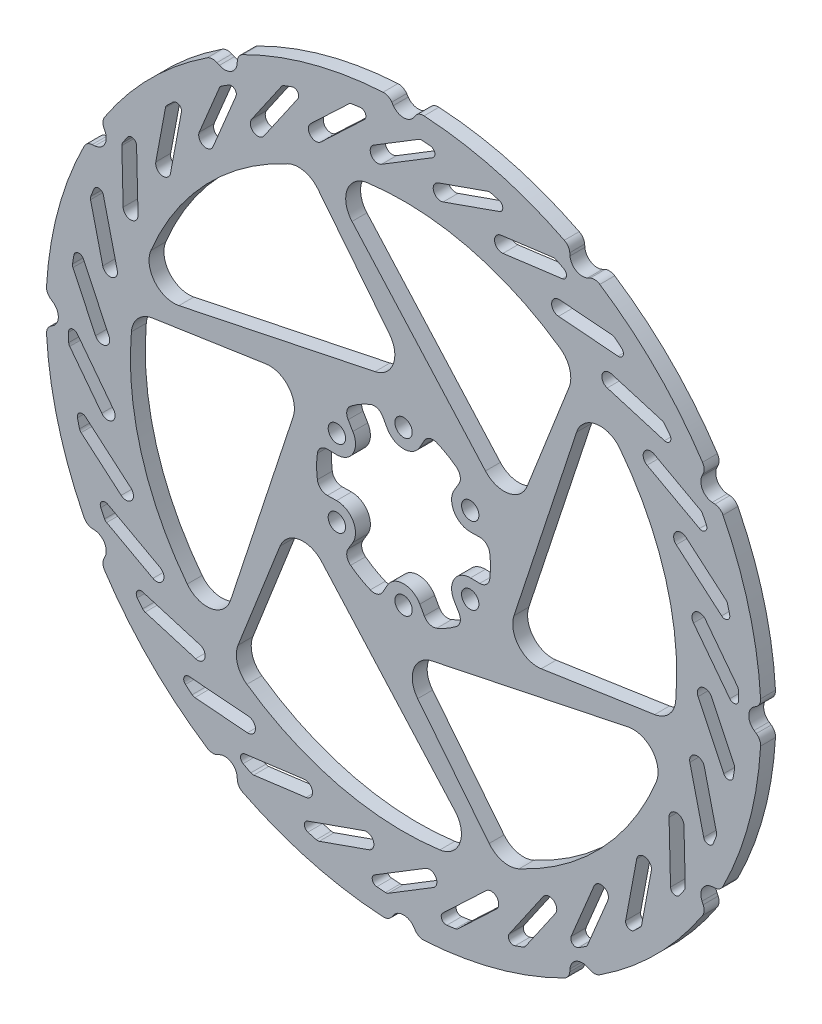
SolidWorks part; units mm, degrees
ref_plane "Front Plane" through (0, 0, 0) normal (0, 0, 1) x (1, 0, 0)
ref_plane "Top Plane" through (0, 0, 0) normal (0, 1, 0) x (1, 0, 0)
ref_plane "Right Plane" through (0, 0, 0) normal (1, 0, 0) x (0, 0, -1)
sketch "Sketch1" plane through (0, 0, 0) normal (0, 0, 1) x (1, 0, 0)
  line L0 (2.0536, 70.5743) -> (2.367, 71.0256)
  line L1 (-2.0536, 70.5743) -> (-2.367, 71.0256)
  line L2 (37.0656, 60.0923) -> (37.5627, 60.3265)
  line L3 (33.5087, 62.1459) -> (33.463, 62.6935)
  line L4 (62.1459, 33.5087) -> (62.6935, 33.463)
  line L5 (60.0923, 37.0656) -> (60.3265, 37.5627)
  line L6 (70.5743, -2.0536) -> (71.0256, -2.367)
  line L7 (70.5743, 2.0536) -> (71.0256, 2.367)
  line L8 (60.0923, -37.0656) -> (60.3265, -37.5627)
  line L9 (62.1459, -33.5087) -> (62.6935, -33.463)
  line L10 (33.5087, -62.1459) -> (33.463, -62.6935)
  line L11 (37.0656, -60.0923) -> (37.5627, -60.3265)
  line L12 (-2.0536, -70.5743) -> (-2.367, -71.0256)
  line L13 (2.0536, -70.5743) -> (2.367, -71.0256)
  line L14 (-37.0656, -60.0923) -> (-37.5627, -60.3265)
  line L15 (-33.5087, -62.1459) -> (-33.463, -62.6935)
  line L16 (-62.1459, -33.5087) -> (-62.6935, -33.463)
  line L17 (-60.0923, -37.0656) -> (-60.3265, -37.5627)
  line L18 (-70.5743, 2.0536) -> (-71.0256, 2.367)
  line L19 (-70.5743, -2.0536) -> (-71.0256, -2.367)
  line L20 (-60.0923, 37.0656) -> (-60.3265, 37.5627)
  line L21 (-62.1459, 33.5087) -> (-62.6935, 33.463)
  line L22 (-33.5087, 62.1459) -> (-33.463, 62.6935)
  line L23 (-37.0656, 60.0923) -> (-37.5627, 60.3265)
  arc A0 (-4.1244, 71.8818) -> (-32.369, 64.3136) centre (0, 0) ccw
  arc A1 (-2.0536, 70.5743) -> (2.0536, 70.5743) centre (0, 72) ccw
  arc A2 (33.5087, 62.1459) -> (37.0656, 60.0923) centre (36, 62.3538) ccw
  arc A3 (60.0923, 37.0656) -> (62.1459, 33.5087) centre (62.3538, 36) ccw
  arc A4 (70.5743, 2.0536) -> (70.5743, -2.0536) centre (72, 0) ccw
  arc A5 (62.1459, -33.5087) -> (60.0923, -37.0656) centre (62.3538, -36) ccw
  arc A6 (37.0656, -60.0923) -> (33.5087, -62.1459) centre (36, -62.3538) ccw
  arc A7 (2.0536, -70.5743) -> (-2.0536, -70.5743) centre (0, -72) ccw
  arc A8 (-33.5087, -62.1459) -> (-37.0656, -60.0923) centre (-36, -62.3538) ccw
  arc A9 (-60.0923, -37.0656) -> (-62.1459, -33.5087) centre (-62.3538, -36) ccw
  arc A10 (-70.5743, -2.0536) -> (-70.5743, 2.0536) centre (-72, 0) ccw
  arc A11 (-62.1459, 33.5087) -> (-60.0923, 37.0656) centre (-62.3538, 36) ccw
  arc A12 (-37.0656, 60.0923) -> (-33.5087, 62.1459) centre (-36, 62.3538) ccw
  arc A13 (32.369, 64.3136) -> (4.1244, 71.8818) centre (0, 0) ccw
  arc A14 (60.1892, 39.5127) -> (39.5127, 60.1892) centre (0, 0) ccw
  arc A15 (71.8818, 4.1244) -> (64.3136, 32.369) centre (0, 0) ccw
  arc A16 (64.3136, -32.369) -> (71.8818, -4.1244) centre (0, 0) ccw
  arc A17 (39.5127, -60.1892) -> (60.1892, -39.5127) centre (0, 0) ccw
  arc A18 (4.1244, -71.8818) -> (32.369, -64.3136) centre (0, 0) ccw
  arc A19 (-32.369, -64.3136) -> (-4.1244, -71.8818) centre (0, 0) ccw
  arc A20 (-60.1892, -39.5127) -> (-39.5127, -60.1892) centre (0, 0) ccw
  arc A21 (-39.5127, 60.1892) -> (-60.1892, 39.5127) centre (0, 0) ccw
  arc A22 (-64.3136, 32.369) -> (-71.8818, 4.1244) centre (0, 0) ccw
  arc A23 (-71.8818, -4.1244) -> (-64.3136, -32.369) centre (0, 0) ccw
  arc A24 (-71.0256, 2.367) -> (-71.8818, 4.1244) centre (-69.8851, 4.0099) cw
  arc A25 (-71.0256, -2.367) -> (-71.8818, -4.1244) centre (-69.8851, -4.0099) ccw
  arc A26 (-62.6935, -33.463) -> (-64.3136, -32.369) centre (-62.5272, -31.4699) cw
  arc A27 (-60.3265, -37.5627) -> (-60.1892, -39.5127) centre (-58.5173, -38.4152) ccw
  arc A28 (-62.6935, 33.463) -> (-64.3136, 32.369) centre (-62.5272, 31.4699) ccw
  arc A29 (-60.3265, 37.5627) -> (-60.1892, 39.5127) centre (-58.5173, 38.4152) cw
  arc A30 (-37.5627, 60.3265) -> (-39.5127, 60.1892) centre (-38.4152, 58.5173) ccw
  arc A31 (-33.463, 62.6935) -> (-32.369, 64.3136) centre (-31.4699, 62.5272) cw
  arc A32 (-37.5627, -60.3265) -> (-39.5127, -60.1892) centre (-38.4152, -58.5173) cw
  arc A33 (-33.463, -62.6935) -> (-32.369, -64.3136) centre (-31.4699, -62.5272) ccw
  arc A34 (-2.367, -71.0256) -> (-4.1244, -71.8818) centre (-4.0099, -69.8851) cw
  arc A35 (2.367, -71.0256) -> (4.1244, -71.8818) centre (4.0099, -69.8851) ccw
  arc A36 (33.463, -62.6935) -> (32.369, -64.3136) centre (31.4699, -62.5272) cw
  arc A37 (37.5627, -60.3265) -> (39.5127, -60.1892) centre (38.4152, -58.5173) ccw
  arc A38 (60.3265, -37.5627) -> (60.1892, -39.5127) centre (58.5173, -38.4152) cw
  arc A39 (62.6935, -33.463) -> (64.3136, -32.369) centre (62.5272, -31.4699) ccw
  arc A40 (71.0256, -2.367) -> (71.8818, -4.1244) centre (69.8851, -4.0099) cw
  arc A41 (71.0256, 2.367) -> (71.8818, 4.1244) centre (69.8851, 4.0099) ccw
  arc A42 (62.6935, 33.463) -> (64.3136, 32.369) centre (62.5272, 31.4699) cw
  arc A43 (60.3265, 37.5627) -> (60.1892, 39.5127) centre (58.5173, 38.4152) ccw
  arc A44 (37.5627, 60.3265) -> (39.5127, 60.1892) centre (38.4152, 58.5173) cw
  arc A45 (33.463, 62.6935) -> (32.369, 64.3136) centre (31.4699, 62.5272) ccw
  arc A46 (2.367, 71.0256) -> (4.1244, 71.8818) centre (4.0099, 69.8851) cw
  arc A47 (-2.367, 71.0256) -> (-4.1244, 71.8818) centre (-4.0099, 69.8851) ccw
  point P64 (0, 0)
  point P110 (3, 71.9375)
  point P113 (-3, 71.9375)
  dimension "D1" = 144
  dimension "D2" = 5
  dimension "D7" = 2
  dimension "D3" = 72
  dimension "D4" = 6
  dimension "D5" = 3
  dimension "D6" = 12
extrude "Boss-Extrude1" add sketch "Sketch1" along normal blind 3
sketch "Sketch2" plane through (0, 0, 3) normal (0, 0, 1) x (1, 0, 0)
  line L0 (3.0631, 67.2567) -> (-5.9927, 61.7243)
  line L1 (5.8342, 65.4341) -> (-4.4287, 59.1642)
  line L2 (16.9796, 65.1501) -> (6.9714, 61.6214)
  line L3 (19.3112, 62.7912) -> (7.969, 58.7921)
  line L4 (30.154, 60.1962) -> (19.6309, 58.8254)
  line L5 (31.9442, 57.404) -> (20.0184, 55.8505)
  line L6 (42.0105, 52.6114) -> (31.4324, 53.4584)
  line L7 (43.1811, 49.508) -> (31.1929, 50.468)
  line L8 (52.031, 42.7272) -> (41.8602, 45.7551)
  line L9 (52.5308, 39.4483) -> (41.0042, 42.8798)
  line L10 (59.7775, 30.9757) -> (50.4584, 36.052)
  line L11 (59.5847, 27.6645) -> (49.0234, 33.4175)
  line L12 (64.9114, 17.8703) -> (56.8514, 24.7733)
  line L13 (64.0344, 14.6716) -> (54.9, 22.4947)
  line L14 (67.2084, 3.984) -> (60.7597, 12.4118)
  line L15 (65.6855, 1.0375) -> (58.3772, 10.5888)
  line L16 (66.5681, -10.0765) -> (62.0125, -0.492)
  line L17 (64.4658, -12.6419) -> (59.303, -1.7799)
  line L18 (63.0184, -23.6966) -> (60.5551, -13.3744)
  line L19 (60.4287, -25.7689) -> (57.6371, -14.0708)
  line L20 (56.7145, -36.281) -> (56.4511, -25.6723)
  line L21 (53.7505, -37.7696) -> (53.4521, -25.7467)
  line L22 (47.9319, -47.2798) -> (49.88, -36.8481)
  line L23 (44.7232, -48.1196) -> (46.931, -36.2974)
  line L24 (37.0544, -56.2122) -> (41.1288, -46.4135)
  line L25 (33.7412, -56.3665) -> (38.3588, -45.2617)
  line L26 (24.5575, -62.6879) -> (30.5801, -53.9505)
  line L27 (21.2847, -62.15) -> (28.1101, -52.2479)
  line L28 (10.9873, -66.4238) -> (18.695, -59.1295)
  line L29 (7.8978, -65.2172) -> (16.6329, -56.9505)
  line L30 (-3.0631, -67.2567) -> (5.9927, -61.7243)
  line L31 (-5.8342, -65.4341) -> (4.4287, -59.1642)
  line L32 (-16.9796, -65.1501) -> (-6.9714, -61.6214)
  line L33 (-19.3112, -62.7912) -> (-7.969, -58.7921)
  line L34 (-30.154, -60.1962) -> (-19.6309, -58.8254)
  line L35 (-31.9442, -57.404) -> (-20.0184, -55.8505)
  line L36 (-42.0105, -52.6114) -> (-31.4324, -53.4584)
  line L37 (-43.1811, -49.508) -> (-31.1929, -50.468)
  line L38 (-52.031, -42.7272) -> (-41.8602, -45.7551)
  line L39 (-52.5308, -39.4483) -> (-41.0042, -42.8798)
  line L40 (-59.7775, -30.9757) -> (-50.4584, -36.052)
  line L41 (-59.5847, -27.6645) -> (-49.0234, -33.4175)
  line L42 (-64.9114, -17.8703) -> (-56.8514, -24.7733)
  line L43 (-64.0344, -14.6716) -> (-54.9, -22.4947)
  line L44 (-67.2084, -3.984) -> (-60.7597, -12.4118)
  line L45 (-65.6855, -1.0375) -> (-58.3772, -10.5888)
  line L46 (-66.5681, 10.0765) -> (-62.0125, 0.492)
  line L47 (-64.4658, 12.6419) -> (-59.303, 1.7799)
  line L48 (-63.0184, 23.6966) -> (-60.5551, 13.3744)
  line L49 (-60.4287, 25.7689) -> (-57.6371, 14.0708)
  line L50 (-56.7145, 36.281) -> (-56.4511, 25.6723)
  line L51 (-53.7505, 37.7696) -> (-53.4521, 25.7467)
  line L52 (-47.9319, 47.2798) -> (-49.88, 36.8481)
  line L53 (-44.7232, 48.1196) -> (-46.931, 36.2974)
  line L54 (-37.0544, 56.2122) -> (-41.1288, 46.4135)
  line L55 (-33.7412, 56.3665) -> (-38.3588, 45.2617)
  line L56 (-24.5575, 62.6879) -> (-30.5801, 53.9505)
  line L57 (-21.2847, 62.15) -> (-28.1101, 52.2479)
  line L58 (-10.9873, 66.4238) -> (-18.695, 59.1295)
  line L59 (-7.8978, 65.2172) -> (-16.6329, 56.9505)
  arc A0 (5.3927, 67.2842) -> (3.6383, 67.4019) centre (0, 0) ccw
  arc A1 (-5.9927, 61.7243) -> (-4.4287, 59.1642) centre (-5.2107, 60.4442) ccw
  arc A2 (5.8342, 65.4341) -> (5.3927, 67.2842) centre (5.3128, 66.2874) ccw
  arc A3 (3.0631, 67.2567) -> (3.6383, 67.4019) centre (3.5844, 66.4033) cw
  arc A4 (19.2641, 64.6927) -> (17.5724, 65.1725) centre (0, 0) ccw
  arc A5 (6.9714, 61.6214) -> (7.969, 58.7921) centre (7.4702, 60.2068) ccw
  arc A6 (19.3112, 62.7912) -> (19.2641, 64.6927) centre (18.9787, 63.7343) ccw
  arc A7 (16.9796, 65.1501) -> (17.5724, 65.1725) centre (17.3121, 64.207) cw
  arc A8 (32.2935, 59.2738) -> (30.7386, 60.0949) centre (0, 0) ccw
  arc A9 (19.6309, 58.8254) -> (20.0184, 55.8505) centre (19.8247, 57.3379) ccw
  arc A10 (31.9442, 57.404) -> (32.2935, 59.2738) centre (31.815, 58.3957) ccw
  arc A11 (30.154, 60.1962) -> (30.7386, 60.0949) centre (30.2832, 59.2046) cw
  arc A12 (43.9115, 51.2643) -> (42.5613, 52.3907) centre (0, 0) ccw
  arc A13 (31.4324, 53.4584) -> (31.1929, 50.468) centre (31.3127, 51.9632) ccw
  arc A14 (43.1811, 49.508) -> (43.9115, 51.2643) centre (43.2609, 50.5049) ccw
  arc A15 (42.0105, 52.6114) -> (42.5613, 52.3907) centre (41.9307, 51.6146) cw
  arc A16 (53.6104, 41.0144) -> (52.5238, 42.3969) centre (0, 0) ccw
  arc A17 (41.8602, 45.7551) -> (41.0042, 42.8798) centre (41.4322, 44.3174) ccw
  arc A18 (52.5308, 39.4483) -> (53.6104, 41.0144) centre (52.8161, 40.4067) ccw
  arc A19 (52.031, 42.7272) -> (52.5238, 42.3969) centre (51.7457, 41.7688) cw
  arc A20 (60.9662, 28.9719) -> (60.1909, 30.5501) centre (0, 0) ccw
  arc A21 (50.4584, 36.052) -> (49.0234, 33.4175) centre (49.7409, 34.7347) ccw
  arc A22 (59.5847, 27.6645) -> (60.9662, 28.9719) centre (60.063, 28.5427) ccw
  arc A23 (59.7775, 30.9757) -> (60.1909, 30.5501) centre (59.2992, 30.0975) cw
  arc A24 (65.6576, 15.6632) -> (65.2273, 17.3681) centre (0, 0) ccw
  arc A25 (56.8514, 24.7733) -> (54.9, 22.4947) centre (55.8757, 23.634) ccw
  arc A26 (64.0344, 14.6716) -> (65.6576, 15.6632) centre (64.6849, 15.4311) ccw
  arc A27 (64.9114, 17.8703) -> (65.2273, 17.3681) centre (64.261, 17.1108) cw
  arc A28 (67.4793, 1.6699) -> (67.4129, 3.4271) centre (0, 0) ccw
  arc A29 (60.7597, 12.4118) -> (58.3772, 10.5888) centre (59.5684, 11.5003) ccw
  arc A30 (65.6855, 1.0375) -> (67.4793, 1.6699) centre (66.4796, 1.6452) ccw
  arc A31 (67.2084, 3.984) -> (67.4129, 3.4271) centre (66.4142, 3.3763) cw
  arc A32 (66.352, -12.3963) -> (66.6523, -10.6638) centre (0, 0) ccw
  arc A33 (62.0125, -0.492) -> (59.303, -1.7799) centre (60.6578, -1.136) ccw
  arc A34 (64.4658, -12.6419) -> (66.352, -12.3963) centre (65.369, -12.2127) ccw
  arc A35 (66.5681, -10.0765) -> (66.6523, -10.6638) centre (65.6649, -10.5058) cw
  arc A36 (62.3247, -25.9208) -> (62.9787, -24.2885) centre (0, 0) ccw
  arc A37 (60.5551, -13.3744) -> (57.6371, -14.0708) centre (59.0961, -13.7226) ccw
  arc A38 (60.4287, -25.7689) -> (62.3247, -25.9208) centre (61.4013, -25.5367) ccw
  arc A39 (63.0184, -23.6966) -> (62.9787, -24.2885) centre (62.0457, -23.9287) cw
  arc A40 (55.5735, -38.3124) -> (56.5526, -36.8518) centre (0, 0) ccw
  arc A41 (56.4511, -25.6723) -> (53.4521, -25.7467) centre (54.9516, -25.7095) ccw
  arc A42 (53.7505, -37.7696) -> (55.5735, -38.3124) centre (54.7502, -37.7448) ccw
  arc A43 (56.7145, -36.281) -> (56.5526, -36.8518) centre (55.7148, -36.3058) cw
  arc A44 (46.3935, -49.0295) -> (47.6549, -47.8044) centre (0, 0) ccw
  arc A45 (49.88, -36.8481) -> (46.931, -36.2974) centre (48.4055, -36.5728) ccw
  arc A46 (44.7232, -48.1196) -> (46.3935, -49.0295) centre (45.7062, -48.3032) ccw
  arc A47 (47.9319, -47.2798) -> (47.6549, -47.8044) centre (46.9489, -47.0962) cw
  arc A48 (35.1859, -57.6039) -> (36.6744, -56.6678) centre (0, 0) ccw
  arc A49 (41.1288, -46.4135) -> (38.3588, -45.2617) centre (39.7438, -45.8376) ccw
  arc A50 (33.7412, -56.3665) -> (35.1859, -57.6039) centre (34.6646, -56.7505) ccw
  arc A51 (37.0544, -56.2122) -> (36.6744, -56.6678) centre (36.1311, -55.8283) cw
  arc A52 (22.4405, -63.6606) -> (24.0911, -63.0545) centre (0, 0) ccw
  arc A53 (30.5801, -53.9505) -> (28.1101, -52.2479) centre (29.3451, -53.0992) ccw
  arc A54 (21.2847, -62.15) -> (22.4405, -63.6606) centre (22.108, -62.7175) ccw
  arc A55 (24.5575, -62.6879) -> (24.0911, -63.0545) centre (23.7342, -62.1204) cw
  arc A56 (8.7143, -66.9351) -> (10.4549, -66.6854) centre (0, 0) ccw
  arc A57 (18.695, -59.1295) -> (16.6329, -56.9505) centre (17.6639, -58.04) ccw
  arc A58 (7.8978, -65.2172) -> (8.7143, -66.9351) centre (8.5852, -65.9435) ccw
  arc A59 (10.9873, -66.4238) -> (10.4549, -66.6854) centre (10.3, -65.6975) cw
  arc A60 (-5.3927, -67.2842) -> (-3.6383, -67.4019) centre (0, 0) ccw
  arc A61 (5.9927, -61.7243) -> (4.4287, -59.1642) centre (5.2107, -60.4442) ccw
  arc A62 (-5.8342, -65.4341) -> (-5.3927, -67.2842) centre (-5.3128, -66.2874) ccw
  arc A63 (-3.0631, -67.2567) -> (-3.6383, -67.4019) centre (-3.5844, -66.4033) cw
  arc A64 (-19.2641, -64.6927) -> (-17.5724, -65.1725) centre (0, 0) ccw
  arc A65 (-6.9714, -61.6214) -> (-7.969, -58.7921) centre (-7.4702, -60.2068) ccw
  arc A66 (-19.3112, -62.7912) -> (-19.2641, -64.6927) centre (-18.9787, -63.7343) ccw
  arc A67 (-16.9796, -65.1501) -> (-17.5724, -65.1725) centre (-17.3121, -64.207) cw
  arc A68 (-32.2935, -59.2738) -> (-30.7386, -60.0949) centre (0, 0) ccw
  arc A69 (-19.6309, -58.8254) -> (-20.0184, -55.8505) centre (-19.8247, -57.3379) ccw
  arc A70 (-31.9442, -57.404) -> (-32.2935, -59.2738) centre (-31.815, -58.3957) ccw
  arc A71 (-30.154, -60.1962) -> (-30.7386, -60.0949) centre (-30.2832, -59.2046) cw
  arc A72 (-43.9115, -51.2643) -> (-42.5613, -52.3907) centre (0, 0) ccw
  arc A73 (-31.4324, -53.4584) -> (-31.1929, -50.468) centre (-31.3127, -51.9632) ccw
  arc A74 (-43.1811, -49.508) -> (-43.9115, -51.2643) centre (-43.2609, -50.5049) ccw
  arc A75 (-42.0105, -52.6114) -> (-42.5613, -52.3907) centre (-41.9307, -51.6146) cw
  arc A76 (-53.6104, -41.0144) -> (-52.5238, -42.3969) centre (0, 0) ccw
  arc A77 (-41.8602, -45.7551) -> (-41.0042, -42.8798) centre (-41.4322, -44.3174) ccw
  arc A78 (-52.5308, -39.4483) -> (-53.6104, -41.0144) centre (-52.8161, -40.4067) ccw
  arc A79 (-52.031, -42.7272) -> (-52.5238, -42.3969) centre (-51.7457, -41.7688) cw
  arc A80 (-60.9662, -28.9719) -> (-60.1909, -30.5501) centre (0, 0) ccw
  arc A81 (-50.4584, -36.052) -> (-49.0234, -33.4175) centre (-49.7409, -34.7347) ccw
  arc A82 (-59.5847, -27.6645) -> (-60.9662, -28.9719) centre (-60.063, -28.5427) ccw
  arc A83 (-59.7775, -30.9757) -> (-60.1909, -30.5501) centre (-59.2992, -30.0975) cw
  arc A84 (-65.6576, -15.6632) -> (-65.2273, -17.3681) centre (0, 0) ccw
  arc A85 (-56.8514, -24.7733) -> (-54.9, -22.4947) centre (-55.8757, -23.634) ccw
  arc A86 (-64.0344, -14.6716) -> (-65.6576, -15.6632) centre (-64.6849, -15.4311) ccw
  arc A87 (-64.9114, -17.8703) -> (-65.2273, -17.3681) centre (-64.261, -17.1108) cw
  arc A88 (-67.4793, -1.6699) -> (-67.4129, -3.4271) centre (0, 0) ccw
  arc A89 (-60.7597, -12.4118) -> (-58.3772, -10.5888) centre (-59.5684, -11.5003) ccw
  arc A90 (-65.6855, -1.0375) -> (-67.4793, -1.6699) centre (-66.4796, -1.6452) ccw
  arc A91 (-67.2084, -3.984) -> (-67.4129, -3.4271) centre (-66.4142, -3.3763) cw
  arc A92 (-66.352, 12.3963) -> (-66.6523, 10.6638) centre (0, 0) ccw
  arc A93 (-62.0125, 0.492) -> (-59.303, 1.7799) centre (-60.6578, 1.136) ccw
  arc A94 (-64.4658, 12.6419) -> (-66.352, 12.3963) centre (-65.369, 12.2127) ccw
  arc A95 (-66.5681, 10.0765) -> (-66.6523, 10.6638) centre (-65.6649, 10.5058) cw
  arc A96 (-62.3247, 25.9208) -> (-62.9787, 24.2885) centre (0, 0) ccw
  arc A97 (-60.5551, 13.3744) -> (-57.6371, 14.0708) centre (-59.0961, 13.7226) ccw
  arc A98 (-60.4287, 25.7689) -> (-62.3247, 25.9208) centre (-61.4013, 25.5367) ccw
  arc A99 (-63.0184, 23.6966) -> (-62.9787, 24.2885) centre (-62.0457, 23.9287) cw
  arc A100 (-55.5735, 38.3124) -> (-56.5526, 36.8518) centre (0, 0) ccw
  arc A101 (-56.4511, 25.6723) -> (-53.4521, 25.7467) centre (-54.9516, 25.7095) ccw
  arc A102 (-53.7505, 37.7696) -> (-55.5735, 38.3124) centre (-54.7502, 37.7448) ccw
  arc A103 (-56.7145, 36.281) -> (-56.5526, 36.8518) centre (-55.7148, 36.3058) cw
  arc A104 (-46.3935, 49.0295) -> (-47.6549, 47.8044) centre (0, 0) ccw
  arc A105 (-49.88, 36.8481) -> (-46.931, 36.2974) centre (-48.4055, 36.5728) ccw
  arc A106 (-44.7232, 48.1196) -> (-46.3935, 49.0295) centre (-45.7062, 48.3032) ccw
  arc A107 (-47.9319, 47.2798) -> (-47.6549, 47.8044) centre (-46.9489, 47.0962) cw
  arc A108 (-35.1859, 57.6039) -> (-36.6744, 56.6678) centre (0, 0) ccw
  arc A109 (-41.1288, 46.4135) -> (-38.3588, 45.2617) centre (-39.7438, 45.8376) ccw
  arc A110 (-33.7412, 56.3665) -> (-35.1859, 57.6039) centre (-34.6646, 56.7505) ccw
  arc A111 (-37.0544, 56.2122) -> (-36.6744, 56.6678) centre (-36.1311, 55.8283) cw
  arc A112 (-22.4405, 63.6606) -> (-24.0911, 63.0545) centre (0, 0) ccw
  arc A113 (-30.5801, 53.9505) -> (-28.1101, 52.2479) centre (-29.3451, 53.0992) ccw
  arc A114 (-21.2847, 62.15) -> (-22.4405, 63.6606) centre (-22.108, 62.7175) ccw
  arc A115 (-24.5575, 62.6879) -> (-24.0911, 63.0545) centre (-23.7342, 62.1204) cw
  arc A116 (-8.7143, 66.9351) -> (-10.4549, 66.6854) centre (0, 0) ccw
  arc A117 (-18.695, 59.1295) -> (-16.6329, 56.9505) centre (-17.6639, 58.04) ccw
  arc A118 (-7.8978, 65.2172) -> (-8.7143, 66.9351) centre (-8.5852, 65.9435) ccw
  arc A119 (-10.9873, 66.4238) -> (-10.4549, 66.6854) centre (-10.3, 65.6975) cw
  point P274 (0, 0)
  dimension "D1" = 135
  dimension "D2" = 1
  dimension "D3" = 1.5
  dimension "D4" = 30
extrude "Cut-Extrude1" cut sketch "Sketch2" against normal up to surface (3 mm away) up to face at (0, 0, 0)
sketch "Sketch3" plane through (0, 0, 3) normal (0, 0, 1) x (1, 0, 0)
  line L0 (3.2761, 13.6753) -> (4.1786, 15.2957)
  line L1 (-3.2761, 13.6753) -> (-4.1786, 15.2957)
  line L2 (10.2051, 9.6749) -> (11.1571, 11.2666)
  line L3 (13.4813, 4.0004) -> (15.3357, 4.0291)
  line L4 (13.4813, -4.0004) -> (15.3357, -4.0291)
  line L5 (10.2051, -9.6749) -> (11.1571, -11.2666)
  line L6 (3.2761, -13.6753) -> (4.1786, -15.2957)
  line L7 (-3.2761, -13.6753) -> (-4.1786, -15.2957)
  line L8 (-10.2051, -9.6749) -> (-11.1571, -11.2666)
  line L9 (-13.4813, -4.0004) -> (-15.3357, -4.0291)
  line L10 (-13.4813, 4.0004) -> (-15.3357, 4.0291)
  line L11 (-10.2051, 9.6749) -> (-11.1571, 11.2666)
  circle A0 centre (0, 0) radius 15.5 construction
  circle A1 centre (0, 15.5) radius 1.75
  circle A2 centre (13.4234, 7.75) radius 1.75
  circle A3 centre (13.4234, -7.75) radius 1.75
  circle A4 centre (0, -15.5) radius 1.75
  circle A5 centre (-13.4234, -7.75) radius 1.75
  circle A6 centre (-13.4234, 7.75) radius 1.75
  arc A7 (-3.2761, 13.6753) -> (3.2761, 13.6753) centre (0, 15.5) ccw
  arc A8 (-6.6905, 16.1706) -> (-10.6589, 13.8794) centre (0, 0) ccw
  arc A9 (10.2051, 9.6749) -> (13.4813, 4.0004) centre (13.4234, 7.75) ccw
  arc A10 (13.4813, -4.0004) -> (10.2051, -9.6749) centre (13.4234, -7.75) ccw
  arc A11 (3.2761, -13.6753) -> (-3.2761, -13.6753) centre (0, -15.5) ccw
  arc A12 (-10.2051, -9.6749) -> (-13.4813, -4.0004) centre (-13.4234, -7.75) ccw
  arc A13 (-13.4813, 4.0004) -> (-10.2051, 9.6749) centre (-13.4234, 7.75) ccw
  arc A14 (-17.3494, 2.2912) -> (-17.3494, -2.2912) centre (0, 0) ccw
  arc A15 (-10.6589, -13.8794) -> (-6.6905, -16.1706) centre (0, 0) ccw
  arc A16 (10.6589, 13.8794) -> (6.6905, 16.1706) centre (0, 0) ccw
  arc A17 (17.3494, -2.2912) -> (17.3494, 2.2912) centre (0, 0) ccw
  arc A18 (6.6905, -16.1706) -> (10.6589, -13.8794) centre (0, 0) ccw
  arc A19 (-4.1786, 15.2957) -> (-6.6905, 16.1706) centre (-5.9259, 14.3225) ccw
  arc A20 (4.1786, 15.2957) -> (6.6905, 16.1706) centre (5.9259, 14.3225) cw
  arc A21 (11.1571, 11.2666) -> (10.6589, 13.8794) centre (9.4407, 12.2932) ccw
  arc A22 (15.3357, 4.0291) -> (17.3494, 2.2912) centre (15.3666, 2.0293) cw
  arc A23 (15.3357, -4.0291) -> (17.3494, -2.2912) centre (15.3666, -2.0293) ccw
  arc A24 (11.1571, -11.2666) -> (10.6589, -13.8794) centre (9.4407, -12.2932) cw
  arc A25 (4.1786, -15.2957) -> (6.6905, -16.1706) centre (5.9259, -14.3225) ccw
  arc A26 (-4.1786, -15.2957) -> (-6.6905, -16.1706) centre (-5.9259, -14.3225) cw
  arc A27 (-11.1571, -11.2666) -> (-10.6589, -13.8794) centre (-9.4407, -12.2932) ccw
  arc A28 (-15.3357, -4.0291) -> (-17.3494, -2.2912) centre (-15.3666, -2.0293) cw
  arc A29 (-15.3357, 4.0291) -> (-17.3494, 2.2912) centre (-15.3666, 2.0293) ccw
  arc A30 (-11.1571, 11.2666) -> (-10.6589, 13.8794) centre (-9.4407, 12.2932) cw
  point P17 (0, 0)
  point P49 (0, 0)
  point P50 (-5, 16.7705)
  point P53 (5, 16.7705)
  dimension "D1" = 31
  dimension "D2" = 3.5
  dimension "D4" = 35
  dimension "D5" = 7.5
  dimension "D9" = 2
  dimension "D6" = 10
  dimension "D7" = 5
  dimension "D3" = 6
  dimension "D8" = 6
extrude "Cut-Extrude2" cut sketch "Sketch3" against normal blind 3
sketch "Sketch4" plane through (0, 0, 3) normal (0, 0, 1) x (1, 0, 0)
  line L0 (-10.3771, 46.2249) -> (16.4924, 16.1474)
  line L1 (24.8744, 17.6488) -> (33.3228, 39.1344)
  line L2 (27.7215, -12.7174) -> (50.5528, -9.2912)
  line L3 (34.8434, 32.0993) -> (22.2303, -6.2091)
  line L4 (2.8471, -30.3663) -> (17.23, -48.4256)
  line L5 (45.2205, -14.1256) -> (5.7379, -22.3565)
  line L6 (-24.8744, -17.6488) -> (-33.3228, -39.1344)
  line L7 (10.3771, -46.2249) -> (-16.4924, -16.1474)
  line L8 (-27.7215, 12.7174) -> (-50.5528, 9.2912)
  line L9 (-34.8434, -32.0993) -> (-22.2303, 6.2091)
  line L10 (-2.8471, 30.3663) -> (-17.23, 48.4256)
  line L11 (-45.2205, 14.1256) -> (-5.7379, 22.3565)
  arc A0 (31.5365, 45.0605) -> (-7.3131, 54.5116) centre (0, 0) ccw
  arc A1 (16.4924, 16.1474) -> (24.8744, 17.6488) centre (20.2212, 19.4785) ccw
  arc A2 (33.3228, 39.1344) -> (31.5365, 45.0605) centre (28.6696, 40.9641) ccw
  arc A3 (-10.3771, 46.2249) -> (-7.3131, 54.5116) centre (-6.6483, 49.556) cw
  arc A4 (22.2303, -6.2091) -> (27.7215, -12.7174) centre (26.9795, -7.7728) ccw
  arc A5 (34.8434, 32.0993) -> (43.5519, 33.5892) centre (39.5926, 30.5356) cw
  arc A6 (54.7918, -4.7812) -> (43.5519, 33.5892) centre (0, 0) ccw
  arc A7 (50.5528, -9.2912) -> (54.7918, -4.7812) centre (49.8107, -4.3465) ccw
  arc A8 (5.7379, -22.3565) -> (2.8471, -30.3663) centre (6.7583, -27.2513) ccw
  arc A9 (45.2205, -14.1256) -> (50.865, -20.9224) centre (46.2409, -19.0204) cw
  arc A10 (23.2553, -49.8417) -> (50.865, -20.9224) centre (0, 0) ccw
  arc A11 (17.23, -48.4256) -> (23.2553, -49.8417) centre (21.1411, -45.3106) ccw
  arc A12 (-16.4924, -16.1474) -> (-24.8744, -17.6488) centre (-20.2212, -19.4785) ccw
  arc A13 (10.3771, -46.2249) -> (7.3131, -54.5116) centre (6.6483, -49.556) cw
  arc A14 (-31.5365, -45.0605) -> (7.3131, -54.5116) centre (0, 0) ccw
  arc A15 (-33.3228, -39.1344) -> (-31.5365, -45.0605) centre (-28.6696, -40.9641) ccw
  arc A16 (-22.2303, 6.2091) -> (-27.7215, 12.7174) centre (-26.9795, 7.7728) ccw
  arc A17 (-34.8434, -32.0993) -> (-43.5519, -33.5892) centre (-39.5926, -30.5356) cw
  arc A18 (-54.7918, 4.7812) -> (-43.5519, -33.5892) centre (0, 0) ccw
  arc A19 (-50.5528, 9.2912) -> (-54.7918, 4.7812) centre (-49.8107, 4.3465) ccw
  arc A20 (-5.7379, 22.3565) -> (-2.8471, 30.3663) centre (-6.7583, 27.2513) ccw
  arc A21 (-45.2205, 14.1256) -> (-50.865, 20.9224) centre (-46.2409, 19.0204) cw
  arc A22 (-23.2553, 49.8417) -> (-50.865, 20.9224) centre (0, 0) ccw
  arc A23 (-17.23, 48.4256) -> (-23.2553, 49.8417) centre (-21.1411, 45.3106) ccw
  point P10 (21.9027, 10.0912)
  point P13 (34.7105, 42.6636)
  point P16 (-16.0717, 52.5994)
  point P62 (0, 0)
  dimension "D2" = 55
  dimension "D4" = 5
  dimension "D1" = 57
  dimension "D3" = 35
  dimension "D5" = 6
extrude "Cut-Extrude3" cut sketch "Sketch4" against normal up to surface (3 mm away) up to face at (-11.6734, 7.75, 0)
